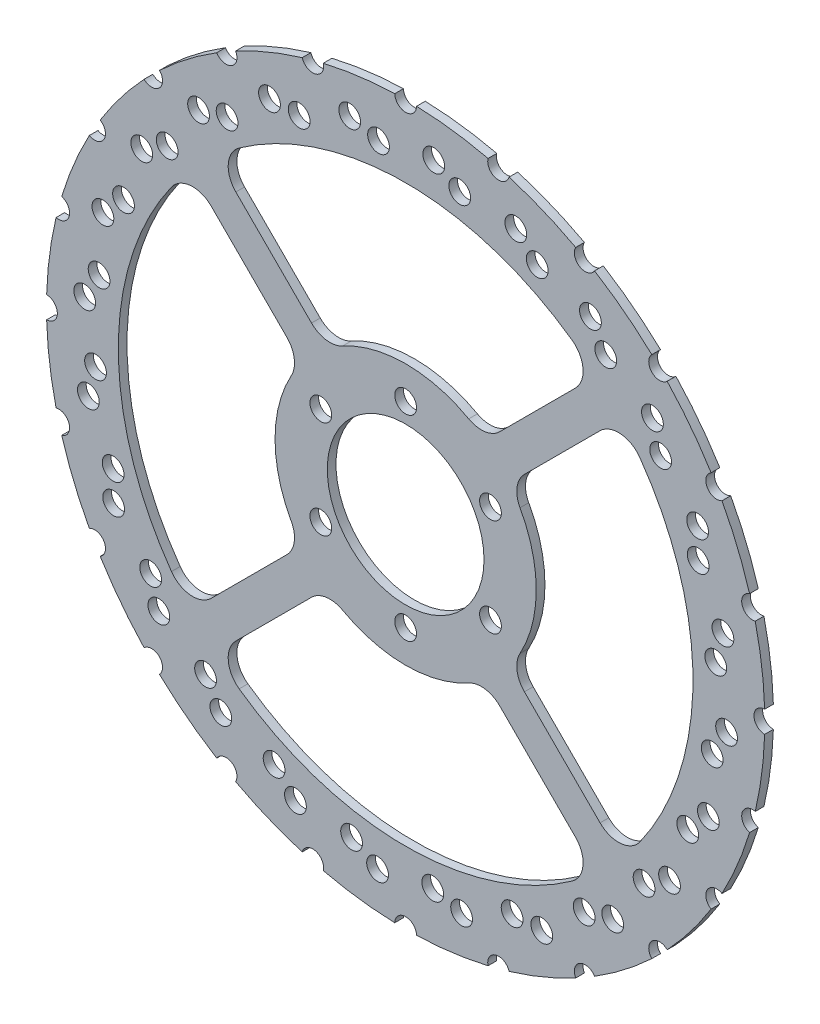
SolidWorks part; units mm, degrees
material "AISI 304"
ref_plane "Front Plane" through (0, 0, 0) normal (0, 0, 1) x (1, 0, 0)
ref_plane "Top Plane" through (0, 0, 0) normal (0, 1, 0) x (1, 0, 0)
ref_plane "Right Plane" through (0, 0, 0) normal (1, 0, 0) x (0, 0, -1)
sketch "Sketch2" plane through (0, 0, 0) normal (0, 0, 1) x (1, 0, 0)
  circle A0 centre (0, 0) radius 82.5
  circle A1 centre (0, 0) radius 18
  dimension "D1" = 165
  dimension "D2" = 36
extrude "Boss-Extrude1" add sketch "Sketch2" along normal blind 2
sketch "Sketch3" plane through (0, 0, 0) normal (0, 0, 1) x (1, 0, 0)
  line L0 (0, 0) -> (0, 82.5) construction
  line L1 (0, 0) -> (7.6318, 87.2314) construction
  line L2 (0, 0) -> (15.3318, 86.9507) construction
  circle A0 centre (0, 0) radius 82.5 construction
  circle A1 centre (0, 0) radius 82.5 construction
  circle A2 centre (0, 0) radius 71.5 construction
  circle A3 centre (0, 0) radius 74 construction
  circle A4 centre (0, 82.5) radius 2.5
  circle A5 centre (6.4495, 73.7184) radius 2.5
  circle A6 centre (12.4158, 70.4138) radius 2.5
  dimension "D3" = 165
  dimension "D4" = 148
  dimension "D5" = 143
  dimension "D6" = 5
  dimension "D7" = 5
  dimension "D8" = 5
  dimension "D1" = 5
  dimension "D2" = 10
extrude "Cut-Extrude1" cut sketch "Sketch3" along normal through all
pattern_circular "CirPattern1" count 24 over 360 about axis through (0, 0, 0) along (0, 0, 1) of "Cut-Extrude1"
sketch "Sketch4" plane through (0, 0, 2) normal (0, 0, 1) x (1, 0, 0)
  circle A0 centre (0, 0) radius 22.5 construction
  circle A1 centre (0, 22.5) radius 2.5
  dimension "D1" = 5
  dimension "D2" = 45
extrude "Cut-Extrude2" cut sketch "Sketch4" against normal through all
pattern_circular "CirPattern2" count 6 over 360 about axis through (0, 0, 0) along (0, 0, 1) of "Cut-Extrude2"
sketch "Sketch5" plane through (0, 0, 2) normal (0, 0, 1) x (1, 0, 0)
  line L0 (0, 0) -> (-75.5477, 75.5477) construction
  line L1 (0, 0) -> (86.3329, 86.3329) construction
  line L2 (0, 0) -> (0, 97.4865) construction
  line L3 (-43.7548, 49.4117) -> (-18.1954, 23.8522)
  line L4 (18.1954, 23.8522) -> (43.7548, 49.4117)
  arc A0 (-43.7548, 49.4117) -> (43.7548, 49.4117) centre (0, 0) cw
  arc A1 (-18.1954, 23.8522) -> (18.1954, 23.8522) centre (0, 0) cw
  dimension "D5" = 66
  dimension "D6" = 30
  dimension "D1" = 45
  dimension "D2" = 45
  dimension "D3" = 8
  dimension "D4" = 8
extrude "Cut-Extrude3" cut sketch "Sketch5" against normal through all
fillet "Fillet1" radius 6 4 edges at (43.7548, 49.4117, 1) (18.1954, 23.8522, 1) (-18.1954, 23.8522, 1) (-43.7548, 49.4117, 1)
pattern_circular "CirPattern3" count 4 over 360 about axis through (0, 0, 0) along (0, 0, 1) of "Cut-Extrude3", "Fillet1"
